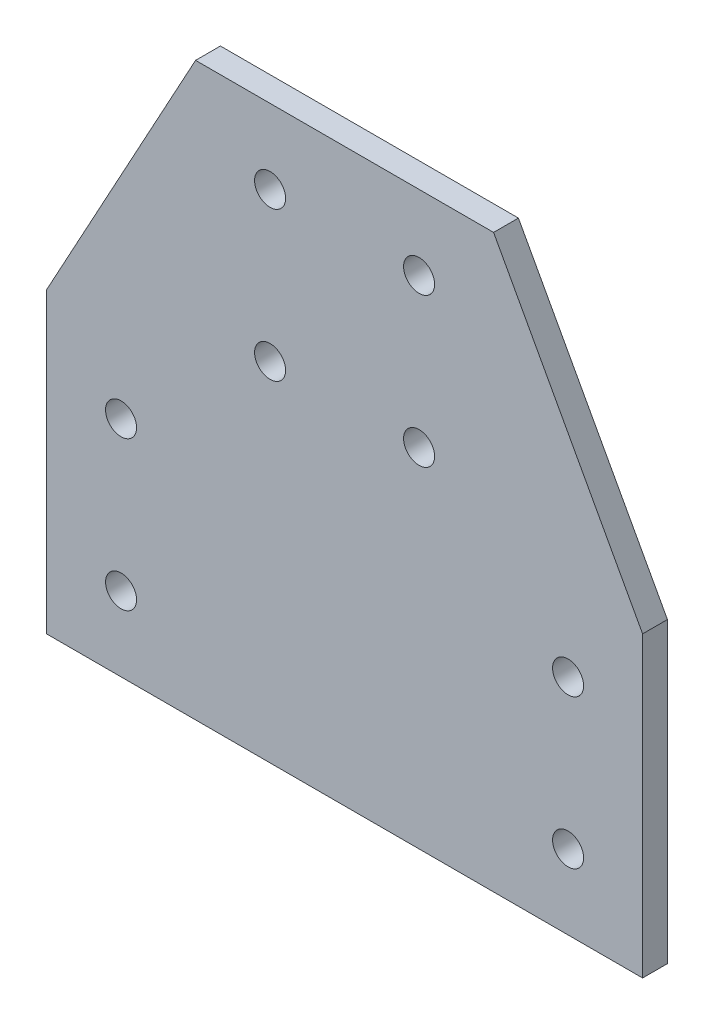
SolidWorks part; units mm, degrees
material "7075-T6, Plate (SS)"
ref_plane "Front Plane" through (0, 0, 0) normal (0, 0, 1) x (1, 0, 0)
ref_plane "Top Plane" through (0, 0, 0) normal (0, 1, 0) x (1, 0, 0)
ref_plane "Right Plane" through (0, 0, 0) normal (1, 0, 0) x (0, 0, -1)
sketch "Sketch1" plane through (0, 0, 0) normal (0, 0, 1) x (1, 0, 0)
  line L0 (57.15, 229.753) -> (57.15, 76.2) construction
  line L1 (0, 0) -> (320.887, 0) construction
  line L2 (0, 0) -> (0, 76.2) construction
  line L3 (0, 76.2) -> (320.887, 76.2) construction
  line L4 (320.887, 0) -> (320.887, 76.2) construction
  line L5 (38.1, 76.2) -> (114.3, 76.2) construction
  line L6 (38.1, 76.2) -> (38.1, 229.753) construction
  line L7 (38.1, 229.753) -> (114.3, 229.753) construction
  line L8 (114.3, 76.2) -> (114.3, 229.753) construction
  line L9 (38.1, 146.05) -> (0, 76.2)
  line L10 (95.25, 229.753) -> (95.25, 76.2) construction
  line L11 (0, 76.2) -> (0, 0)
  line L12 (0, 57.15) -> (320.887, 57.15) construction
  line L14 (0, 19.05) -> (320.887, 19.05) construction
  line L15 (152.4, 0) -> (152.4, 76.2)
  line L16 (152.4, 76.2) -> (114.3, 146.05)
  line L17 (114.3, 146.05) -> (38.1, 146.05)
  line L21 (152.4, 0) -> (0, 0)
  line L22 (57.15, 127) -> (95.25, 127)
  line L23 (57.15, 127) -> (57.15, 88.9)
  line L24 (57.15, 88.9) -> (95.25, 88.9)
  line L25 (95.25, 127) -> (95.25, 88.9)
  line L26 (19.05, 57.15) -> (133.35, 57.15)
  line L27 (19.05, 57.15) -> (19.05, 19.05)
  line L28 (19.05, 19.05) -> (133.35, 19.05)
  line L29 (133.35, 57.15) -> (133.35, 19.05)
  point P24 (76.2, 146.05)
  point P29 (76.2, 0)
  dimension "D1" = 76.2
  dimension "D2" = 76.2
  dimension "D3" = 19.05
  dimension "D4" = 19.05
  dimension "D5" = 19.05
  dimension "D6" = 19.05
  dimension "D7" = 19.05
  dimension "D8" = 19.05
  dimension "D9" = 19.05
  dimension "D10" = 38.1
  dimension "D11" = 12.7
  dimension "D12" = 19.05
extrude "Boss-Extrude1" add sketch "Sketch1" along normal blind 6.35 contours L29 L26 L27 L28 | L25 L22 L23 L24 | L21 L15 L16 L17 L9 L11 L22 L25 L24 L23 L26 L29 L28 L27
hole_wizard "5/16 (0.3125) Diameter Hole1" positions "Sketch2" profile "Sketch3" hole size "5/16" standard "ANSI Inch" end condition through all
sketch "Sketch2" plane through (0, 0, 6.35) normal (0, 0, 1) x (1, 0, 0)
  point P0 (19.05, 19.05)
  point P3 (19.05, 57.15)
  point P6 (57.15, 88.9)
  point P9 (57.15, 127)
  point P12 (95.25, 127)
  point P15 (95.25, 88.9)
  point P18 (133.35, 57.15)
  point P21 (133.35, 19.05)
sketch "Sketch3" plane through (19.05, 19.05, 6.35) normal (1, 0, 0) x (0, -1, 0)
  line L0 (0, 0) -> (0, 6.35)
  line L1 (0, 6.35) -> (3.9687, 6.35)
  line L2 (3.9687, 6.35) -> (3.9687, 0)
  line L5 (3.9687, 0) -> (0, 0)
  line L11 (0, -6.35) -> (0, 107.95) construction
  dimension "Thru Hole Dia." = 7.9375
  dimension "Thru Hole Depth" = 6.35
fillet "Fillet1" [suppressed] radius 19.05
